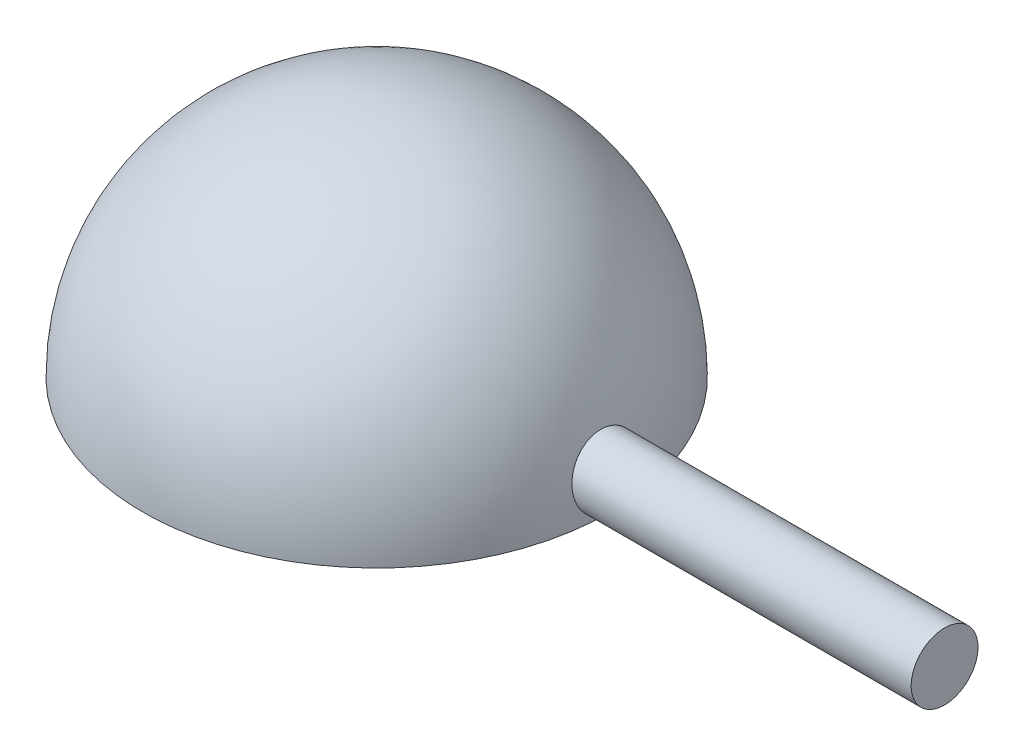
SolidWorks part; units mm, degrees
ref_plane "Front Plane" through (0, 0, 0) normal (0, 0, 1) x (1, 0, 0)
ref_plane "Top Plane" through (0, 0, 0) normal (0, 1, 0) x (1, 0, 0)
ref_plane "Right Plane" through (0, 0, 0) normal (1, 0, 0) x (0, 0, -1)
sketch "boog" plane through (0, 0, 0) normal (0, 0, 1) x (1, 0, 0)
  line L0 (-35, 0) -> (-33, 0)
  line L2 (0, 0) -> (0, 33) construction
  line L3 (0, 33) -> (0, 35)
  arc A0 (0, 33) -> (-33, 0) centre (0, 0) ccw
  arc A1 (0, 35) -> (-35, 0) centre (0, 0) ccw
  dimension "D1" = 2
  dimension "D2" = 35
revolve "bol_half" add sketch "boog" angle 360 about L2
ref_plane "Plane1" through (35, 0, 0) normal (1, 0, 0) x (0, 0, -1)
sketch "cirkel" plane through (35, 0, 0) normal (1, 0, 0) x (0, 0, -1)
  line L0 (-35, 0) -> (35, 0) construction
  line L1 (0, 0) -> (0, 5) construction
  circle A0 centre (0, 5) radius 5
  dimension "D1" = 10
extrude "arm" add sketch "cirkel" along normal blind 50 and the other way up to next
